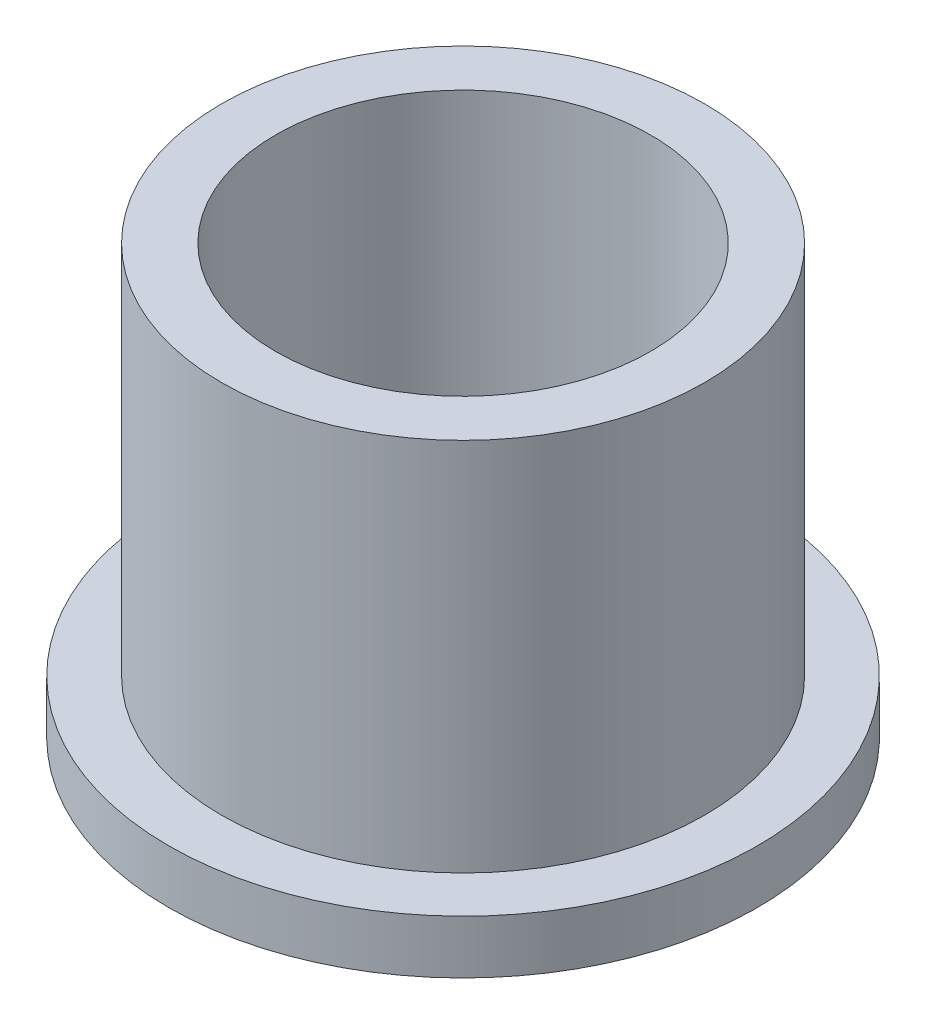
SolidWorks part; units mm, degrees
ref_plane "Front" through (0, 0, 0) normal (0, 0, 1) x (1, 0, 0)
ref_plane "Top" through (0, 0, 0) normal (0, 1, 0) x (1, 0, 0)
ref_plane "Right" through (0, 0, 0) normal (1, 0, 0) x (0, 0, -1)
sketch "Sketch1" plane through (0, 0, 0) normal (0, 1, 0) x (1, 0, 0)
  circle A0 centre (0, 0) radius 5.5626
  circle A1 centre (0, 0) radius 7.1628
  circle A2 centre (0, 0) radius 8.7312
  dimension "ID" = 11.1252
  dimension "OD" = 14.3256
  dimension "FlangeOD" = 17.4625
sketch "Sketch2" plane through (0, 0, 0) normal (0, 1, 0) x (1, 0, 0)
  circle A0 centre (0, 0) radius 5.5626 construction
  circle A1 centre (0, 0) radius 7.1628 construction
  circle A2 centre (0, 0) radius 5.5626
  circle A3 centre (0, 0) radius 7.1628
extrude "Boss-Extrude1" add sketch "Sketch2" along normal blind 12.7
sketch "Sketch3" plane through (0, 0, 0) normal (0, 1, 0) x (1, 0, 0)
  circle A0 centre (0, 0) radius 8.7312 construction
  circle A1 centre (0, 0) radius 7.1628 construction
  circle A2 centre (0, 0) radius 8.7312
  circle A3 centre (0, 0) radius 7.1628
extrude "Boss-Extrude2" add sketch "Sketch3" along normal blind 1.5875
